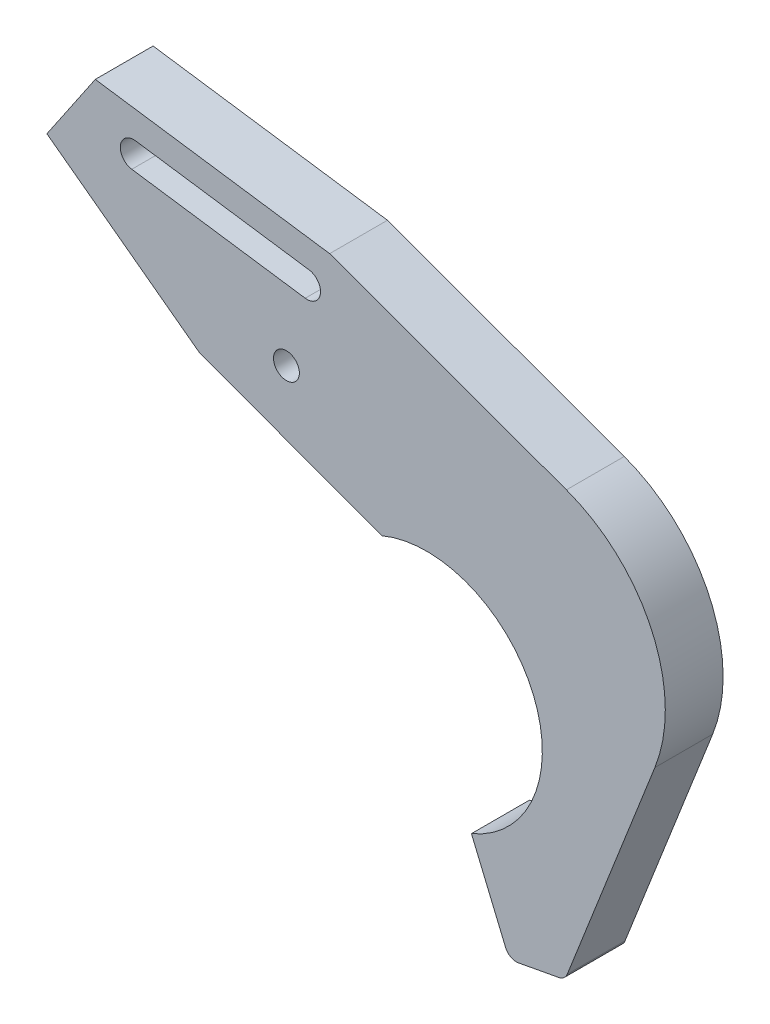
SolidWorks part; units mm, degrees
ref_plane "Front Plane" through (0, 0, 0) normal (0, 0, 1) x (1, 0, 0)
ref_plane "Top Plane" through (0, 0, 0) normal (0, 1, 0) x (1, 0, 0)
ref_plane "Right Plane" through (0, 0, 0) normal (1, 0, 0) x (0, 0, -1)
sketch "Sketch1" plane through (0, 0, 0) normal (0, 0, 1) x (1, 0, 0)
  line L0 (-21.6036, 84.9696) -> (29.8798, 77.5642)
  line L10 (1.3213, 44.3951) -> (-32.2313, 69.3078)
  line L11 (-32.2313, 69.3078) -> (-21.6036, 84.9696)
  line L12 (24.9355, 69.3079) -> (-13.1645, 74.7882) construction
  line L13 (24.517, 66.3984) -> (-13.583, 71.8787)
  line L14 (25.354, 72.2175) -> (-12.746, 77.6978)
  line L15 (109.0358, 35.1262) -> (95.2803, 0.1457)
  line L16 (109.0358, 35.1262) -> (113.414, 47.1517)
  line L17 (113.414, 47.1517) -> (29.8798, 77.5642)
  line L18 (95.2803, 0.1457) -> (81.5668, -34.728)
  line L21 (41.3736, 29.6403) -> (1.3213, 44.3951)
  line L25 (61.0265, -17.2042) -> (41.3736, 29.6403) construction
  line L33 (61.0265, -17.2042) -> (69.3335, -37.0049)
  line L34 (81.5668, -34.728) -> (69.3335, -37.0049)
  circle A0 centre (20.3901, 51.503) radius 2.8384
  arc A1 (24.517, 66.3984) -> (25.354, 72.2175) centre (24.9355, 69.3079) ccw
  arc A2 (-12.746, 77.6978) -> (-13.583, 71.8787) centre (-13.1645, 74.7882) ccw
  arc A4 (61.0265, -17.2042) -> (53.9268, 31.4713) centre (51.2, 6.218) ccw
  arc A5 (53.9268, 31.4713) -> (41.3736, 29.6403) centre (51.2, 6.218) ccw
  circle A6 centre (51.2, 6.218) radius 25.4 construction
  point P16 (5.8855, 72.0481)
  dimension "D1" = 12.7
  dimension "D2" = 25.4
  dimension "D3" = 168.18
  dimension "D4" = 38.1
extrude "Boss-Extrude2" add sketch "Sketch1" along normal blind 12.7
fillet "Fillet5" radius 33.02 1 edges at (113.414, 47.1517, 6.35)
fillet "Fillet7" radius 2.54 2 edges at (69.3335, -37.0049, 6.35) (81.5668, -34.728, 6.35)
